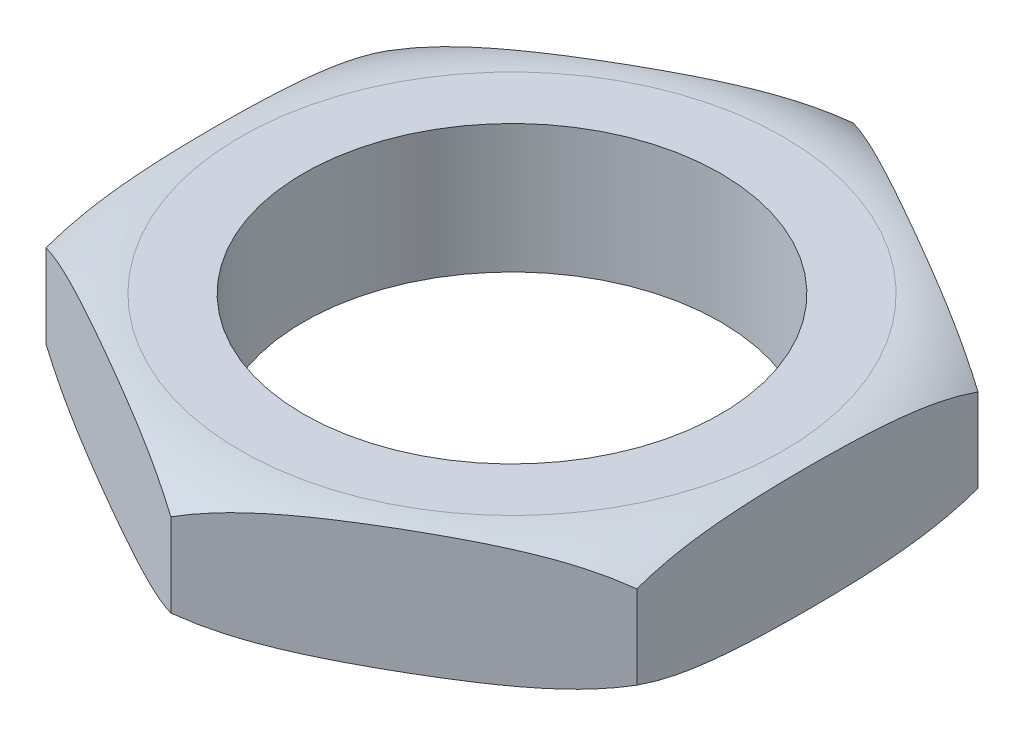
SolidWorks part; units mm, degrees
ref_plane "Alzado" through (0, 0, 0) normal (0, 0, 1) x (1, 0, 0)
ref_plane "Planta" through (0, 0, 0) normal (0, 1, 0) x (1, 0, 0)
ref_plane "Vista lateral" through (0, 0, 0) normal (1, 0, 0) x (0, 0, -1)
sketch "Croquis1" plane through (0, 0, 0) normal (0, 1, 0) x (1, 0, 0)
  line L1 (0, 9.815) -> (-8.5, 4.9075)
  line L2 (-8.5, 4.9075) -> (-8.5, -4.9075)
  line L3 (-8.5, -4.9075) -> (0, -9.815)
  line L4 (0, -9.815) -> (8.5, -4.9075)
  line L5 (8.5, -4.9075) -> (8.5, 4.9075)
  line L6 (8.5, 4.9075) -> (0, 9.815)
  circle A0 centre (0, 0) radius 6
  circle A1 centre (0, 0) radius 8.5 construction
  dimension "D1" = 12
  dimension "D2" = 17
extrude "Saliente-Extruir1" add sketch "Croquis1" along normal blind 3.7
sketch "Croquis2" plane through (0, 0, 0) normal (1, 0, 0) x (0, 0, -1)
  line L0 (9.815, 3.7) -> (9.815, 0) construction
  line L2 (4.9075, 0) -> (9.815, 0) construction
  line L3 (10.9223, 1.85) -> (-3.3423, 1.85) construction
  line L4 (4.9075, 3.7) -> (9.815, 3.7) construction
  line L5 (-4.9075, 3.7) -> (4.9075, 3.7) construction
  line L6 (7.815, 3.7) -> (9.815, 3.7)
  line L7 (9.815, 3.7) -> (9.815, 3.05)
  line L8 (9.815, 0.65) -> (9.815, 0)
  line L9 (9.815, 0) -> (7.815, 0)
  line L10 (0, 0) -> (0, 5.2819) construction
  arc A0 (9.815, 3.05) -> (7.815, 3.7) centre (7.815, 0.2981) ccw
  arc A1 (9.815, 0.65) -> (7.815, 0) centre (7.815, 3.4019) cw
  dimension "D2" = 2
  dimension "D1" = 2.4
revolve "Cortar-Revolución1" cut sketch "Croquis2" angle 360 about L10
